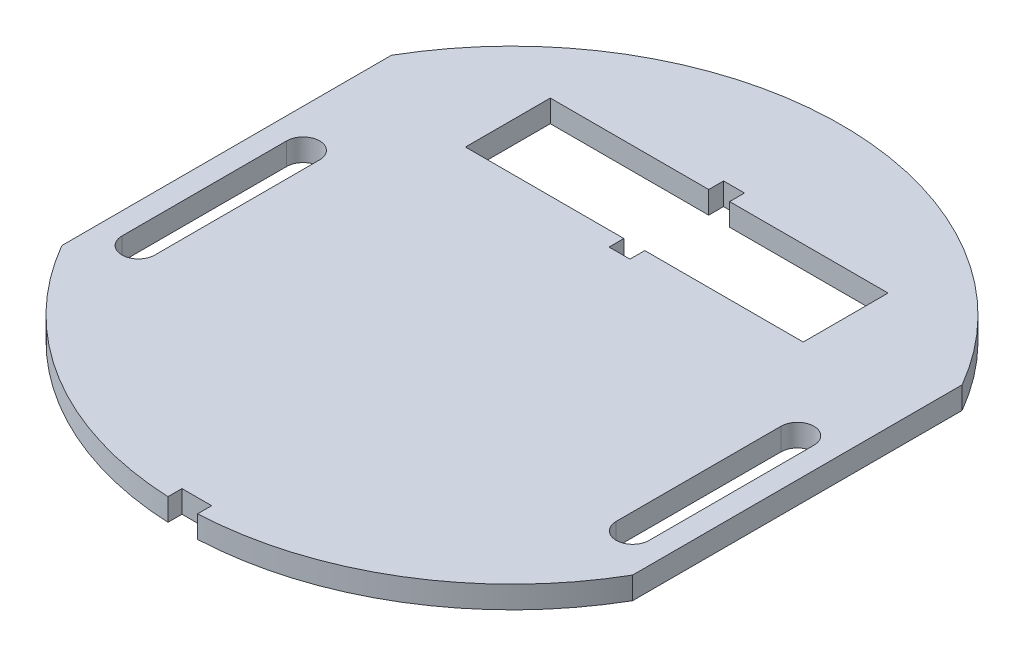
SolidWorks part; units mm, degrees
ref_plane "Front Plane" through (0, 0, 0) normal (0, 0, 1) x (1, 0, 0)
ref_plane "Top Plane" through (0, 0, 0) normal (0, 1, 0) x (1, 0, 0)
ref_plane "Right Plane" through (0, 0, 0) normal (1, 0, 0) x (0, 0, -1)
sketch "Sketch1" plane through (0, 0, 0) normal (0, 1, 0) x (1, 0, 0)
  line L0 (34.641, 20) -> (34.641, -20)
  line L1 (-34.641, 20) -> (-34.641, -20)
  line L2 (0, 40) -> (0, -40) construction
  arc A0 (-34.641, -20) -> (34.641, -20) centre (0, 0) ccw
  arc A1 (34.641, 20) -> (-34.641, 20) centre (0, 0) ccw
  dimension "D1" = 80
  dimension "D2" = 60
extrude "Base" add sketch "Sketch1" along normal blind 2.7
sketch "Sketch2" plane through (0, 2.7, 0) normal (0, 1, 0) x (-1, 0, 0)
  line L0 (30, -4.65) -> (30, 15.35) construction
  line L1 (28, -4.65) -> (28, 15.35)
  line L2 (32, -4.65) -> (32, 15.35)
  arc A0 (28, -4.65) -> (32, -4.65) centre (30, -4.65) ccw
  arc A1 (32, 15.35) -> (28, 15.35) centre (30, 15.35) ccw
  point P2 (30, 5.35)
  dimension "D1" = 20
  dimension "D2" = 5.35
  dimension "D3" = 4
  dimension "D4" = 28
extrude "Wheel Hole" cut sketch "Sketch2" against normal up to next
sketch "Sketch4" plane through (0, 2.7, 0) normal (0, 1, 0) x (-1, 0, 0)
  line L0 (34.641, -20) -> (-34.641, -20) construction
  line L1 (0, 40) -> (0, -40) construction
  arc A0 (-34.641, -20) -> (34.641, -20) centre (0, 0) ccw construction
  arc A1 (34.641, 20) -> (-34.641, 20) centre (0, 0) ccw construction
sketch "Sketch6" plane through (0, 2.7, 0) normal (0, 1, 0) x (-1, 0, 0)
  line L0 (1.27, -14.85) -> (1.27, -13.05)
  line L1 (1.27, -26.95) -> (-1.27, -26.95)
  line L2 (1.27, -26.95) -> (1.27, -25.15)
  line L3 (1.27, -13.05) -> (-1.27, -13.05)
  line L4 (-1.27, -26.95) -> (-1.27, -25.15)
  line L5 (20.5, -25.15) -> (1.27, -25.15)
  line L6 (20.5, -25.15) -> (20.5, -14.85)
  line L7 (20.5, -14.85) -> (1.27, -14.85)
  line L8 (-20.5, -25.15) -> (-20.5, -14.85)
  line L9 (-1.27, -14.85) -> (-1.27, -13.05)
  line L10 (-1.27, -25.15) -> (-20.5, -25.15)
  line L11 (-1.27, -14.85) -> (-20.5, -14.85)
  line L12 (1.27, -25.15) -> (-1.27, -14.85) construction
  line L13 (-1.27, -25.15) -> (1.27, -14.85) construction
  line L14 (34.641, -20) -> (-34.641, -20) construction
  point P12 (0, -20)
  point P15 (0, -20)
  dimension "D1" = 2.54
  dimension "D2" = 13.9
  dimension "D3" = 10.3
  dimension "D4" = 41
extrude "Battery Hole" cut sketch "Sketch6" against normal up to next
ref_plane "Battery Holder Ref Plane" [suppressed] through (-20.5, 0, 0) normal (1, 0, 0) x (0, 0, -1)
sketch "Sketch3" [suppressed] plane through (-20.5, 0, 0) normal (1, 0, 0) x (0, 0, -1)
  line L0 (23.375, 2.7) -> (23.375, 10.2)
  line L1 (31.75, 2.7) -> (15.875, 2.7) construction
  line L2 (8.375, 10.2) -> (8.375, 2.7)
  line L3 (15.875, 2.7) -> (-15.875, 2.7) construction
  line L4 (15.875, 17.7) -> (15.875, 2.7) construction
  line L5 (23.375, 2.7) -> (8.375, 2.7)
  arc A0 (23.375, 10.2) -> (8.375, 10.2) centre (15.875, 10.2) ccw
  circle A1 centre (15.875, 10.2) radius 2.5
  dimension "D1" = 7.5
  dimension "D3" = 5
  dimension "D2" = 7.5
extrude "Battery Holder" [suppressed] add sketch "Sketch3" against normal blind 2.7
sketch "Sketch5" plane through (0, 2.7, 0) normal (0, 1, 0) x (-1, 0, 0)
  line L0 (-1.8, 39.9595) -> (-1.8, 38.2595)
  line L1 (-1.8, 38.2595) -> (1.8, 38.2595)
  line L2 (1.8, 38.2595) -> (1.8, 39.9595)
  line L4 (0, 40) -> (0, -40) construction
  arc A0 (34.641, 20) -> (-34.641, 20) centre (0, 0) ccw construction
  point P5 (0, 38.2595)
  dimension "D1" = 3.6
  dimension "D2" = 1.7
mirror "Mirror" about plane through (0, 0, 0) normal (1, 0, 0) of "Wheel Hole"
extrude "IR Sensor Divot" cut sketch "Sketch5" against normal through all and the other way through all
